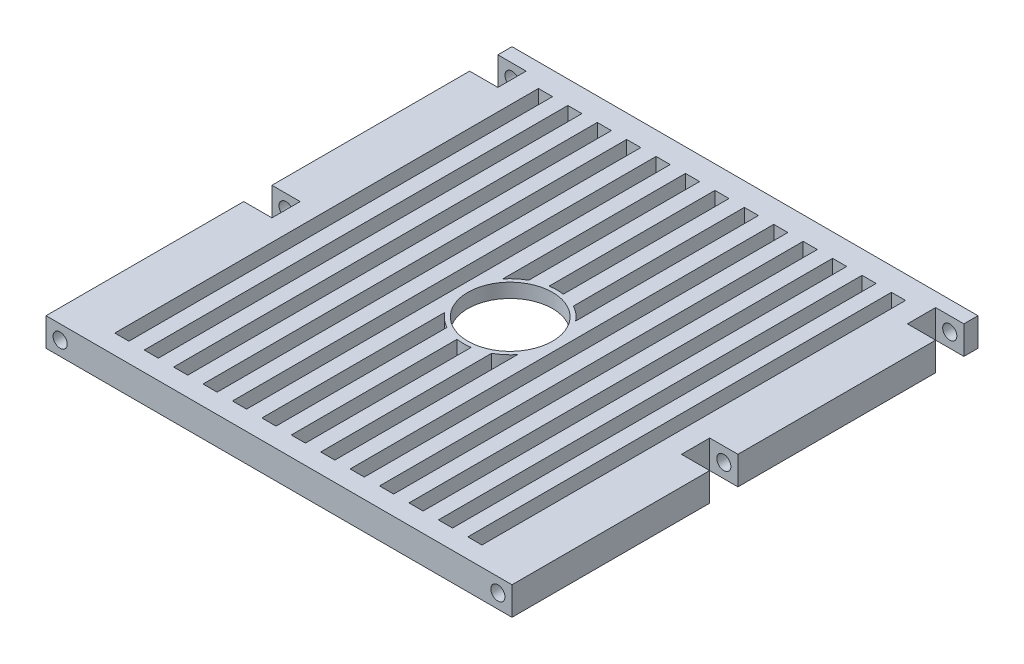
SolidWorks part; units mm, degrees
ref_plane "Plan de face" through (0, 0, 0) normal (0, 0, 1) x (1, 0, 0)
ref_plane "Plan de dessus" through (0, 0, 0) normal (0, 1, 0) x (1, 0, 0)
ref_plane "Plan de droite" through (0, 0, 0) normal (1, 0, 0) x (0, 0, -1)
sketch "Esquisse1" plane through (0, 0, 0) normal (0, 1, 0) x (1, 0, 0)
  line L0 (-82.5, 77.5) -> (-72.5, 77.5)
  line L1 (82.5, 82.5) -> (-82.5, 82.5)
  line L2 (82.5, 82.5) -> (82.5, 77.5)
  line L3 (82.5, -82.5) -> (-82.5, -82.5)
  line L4 (-82.5, 82.5) -> (-82.5, 77.5)
  line L5 (82.5, 82.5) -> (-82.5, -82.5) construction
  line L6 (82.5, -82.5) -> (-82.5, 82.5) construction
  line L7 (-72.5, 77.5) -> (-72.5, 67.5)
  line L8 (-72.5, 67.5) -> (-82.5, 67.5)
  line L9 (-82.5, -2.5) -> (-72.5, -2.5)
  line L10 (-72.5, -2.5) -> (-72.5, -12.5)
  line L11 (-72.5, -12.5) -> (-82.5, -12.5)
  line L12 (-82.5, -2.5) -> (-72.5, -12.5) construction
  line L13 (-72.5, -12.5) -> (-72.5448, -12.5817) construction
  line L14 (-82.5, 67.5) -> (-82.5, -2.5)
  line L15 (-82.5, -12.5) -> (-82.5, -82.5)
  line L16 (0, 16.0212) -> (0, -17.3175) construction
  line L17 (72.5, -12.5) -> (82.5, -12.5)
  line L18 (72.5, -2.5) -> (72.5, -12.5)
  line L19 (82.5, -2.5) -> (72.5, -2.5)
  line L20 (72.5, 77.5) -> (72.5, 67.5)
  line L21 (82.5, 77.5) -> (72.5, 77.5)
  line L22 (72.5, 67.5) -> (82.5, 67.5)
  line L23 (82.5, 67.5) -> (82.5, -2.5)
  line L24 (82.5, -12.5) -> (82.5, -82.5)
  line L25 (60, 74.3519) -> (60, -75.6481)
  line L26 (60, -75.6481) -> (65, -75.6481)
  line L27 (65, 74.3519) -> (65, -75.6481)
  line L28 (65, 74.3519) -> (60, 74.3519)
  line L29 (0, -0.6481) -> (73.9964, -0.6481) construction
  line L30 (49.5833, 74.3519) -> (49.5833, -75.6481)
  line L31 (54.5833, -75.6481) -> (54.5833, 74.3519)
  line L32 (54.5833, 74.3519) -> (49.5833, 74.3519)
  line L33 (49.5833, -75.6481) -> (54.5833, -75.6481)
  line L34 (39.1667, 74.3519) -> (39.1667, -75.6481)
  line L35 (44.1667, -75.6481) -> (44.1667, 74.3519)
  line L36 (44.1667, 74.3519) -> (39.1667, 74.3519)
  line L37 (39.1667, -75.6481) -> (44.1667, -75.6481)
  line L38 (28.75, 74.3519) -> (28.75, -75.6481)
  line L39 (33.75, -75.6481) -> (33.75, 74.3519)
  line L40 (33.75, 74.3519) -> (28.75, 74.3519)
  line L41 (28.75, -75.6481) -> (33.75, -75.6481)
  line L42 (18.3333, 74.3519) -> (18.3333, -75.6481)
  line L43 (23.3333, -75.6481) -> (23.3333, 74.3519)
  line L44 (23.3333, 74.3519) -> (18.3333, 74.3519)
  line L45 (18.3333, -75.6481) -> (23.3333, -75.6481)
  line L46 (7.9167, 74.3519) -> (7.9167, 12.0926)
  line L47 (12.9167, -75.6481) -> (12.9167, -8.2744)
  line L48 (12.9167, 74.3519) -> (7.9167, 74.3519)
  line L49 (7.9167, -75.6481) -> (12.9167, -75.6481)
  line L50 (-2.5, 74.3519) -> (-2.5, 14.1421)
  line L51 (2.5, -75.6481) -> (2.5, -15.4383)
  line L52 (2.5, 74.3519) -> (-2.5, 74.3519)
  line L53 (-2.5, -75.6481) -> (2.5, -75.6481)
  line L54 (-12.9167, 74.3519) -> (-12.9167, 6.9781)
  line L55 (-7.9167, -75.6481) -> (-7.9167, -13.3888)
  line L56 (-7.9167, 74.3519) -> (-12.9167, 74.3519)
  line L57 (-12.9167, -75.6481) -> (-7.9167, -75.6481)
  line L58 (-23.3333, 74.3519) -> (-23.3333, -75.6481)
  line L59 (-18.3333, -75.6481) -> (-18.3333, 74.3519)
  line L60 (-18.3333, 74.3519) -> (-23.3333, 74.3519)
  line L61 (-23.3333, -75.6481) -> (-18.3333, -75.6481)
  line L62 (-33.75, 74.3519) -> (-33.75, -75.6481)
  line L63 (-28.75, -75.6481) -> (-28.75, 74.3519)
  line L64 (-28.75, 74.3519) -> (-33.75, 74.3519)
  line L65 (-33.75, -75.6481) -> (-28.75, -75.6481)
  line L66 (-44.1667, 74.3519) -> (-44.1667, -75.6481)
  line L67 (-39.1667, -75.6481) -> (-39.1667, 74.3519)
  line L68 (-39.1667, 74.3519) -> (-44.1667, 74.3519)
  line L69 (-44.1667, -75.6481) -> (-39.1667, -75.6481)
  line L70 (-54.5833, 74.3519) -> (-54.5833, -75.6481)
  line L71 (-49.5833, -75.6481) -> (-49.5833, 74.3519)
  line L72 (-49.5833, 74.3519) -> (-54.5833, 74.3519)
  line L73 (-54.5833, -75.6481) -> (-49.5833, -75.6481)
  line L74 (-65, 74.3519) -> (-65, -75.6481)
  line L75 (-60, -75.6481) -> (-60, 74.3519)
  line L76 (-60, 74.3519) -> (-65, 74.3519)
  line L77 (-65, -75.6481) -> (-60, -75.6481)
  line L78 (12.9167, 6.9781) -> (12.9167, 74.3519)
  line L79 (7.9167, -13.3888) -> (7.9167, -75.6481)
  line L80 (2.5, 14.1421) -> (2.5, 74.3519)
  line L81 (-12.9167, -8.2744) -> (-12.9167, -75.6481)
  line L82 (-7.9167, 12.0926) -> (-7.9167, 74.3519)
  line L83 (-2.5, -15.4383) -> (-2.5, -75.6481)
  circle A0 centre (0, -0.6481) radius 15
  circle A1 centre (0, -0.6481) radius 16.5
  point P0 (0, 0)
  point P12 (-77.5, -7.5)
  point P32 (60, -0.6481)
  dimension "D9" = 30
  dimension "D15" = 1.5
  dimension "D1" = 165
  dimension "D2" = 165
  dimension "D3" = 5
  dimension "D4" = 10
  dimension "D5" = 10
  dimension "D6" = 10
  dimension "D7" = 10
  dimension "D8" = 90
  dimension "D10" = 5
  dimension "D11" = 150
  dimension "D12" = 60
  dimension "D14" = 65
  dimension "D13" = 13
extrude "BASE" add sketch "Esquisse1" along normal blind 10 contours L24 L17 L18 L19 L23 L22 L20 L21 L2 L1 L4 L0 L7 L8 L14 L9 L10 L11 L15 L3 A0 L51 L53 L83 L55 L57 L81 L54 L56 L82 L50 L52 L80 L46 L48 L78 L47 L49 L79 L77 L74 L76 L75 | L54 A1 L81 A0
sketch "Esquisse5" plane through (0, 0, 12.5) normal (0, 0, -1) x (-1, 0, 0)
  line L0 (-82.5, 10) -> (-72.5, 0) construction
  line L1 (-82.5, 0) -> (82.5, 0) construction
  line L2 (-72.5, 0) -> (-72.5, 10) construction
  line L3 (-82.5, 10) -> (82.5, 10) construction
  line L4 (-72.5, 10) -> (-82.5, 0) construction
  line L5 (-82.5, 10) -> (-82.5, 0) construction
  line L6 (0, 13.0138) -> (0, -4.3994) construction
  line L7 (72.5, 10) -> (82.5, 0) construction
  line L8 (72.5, 0) -> (72.5, 10) construction
  line L9 (82.5, 10) -> (72.5, 0) construction
  circle A0 centre (-77.5, 5) radius 2.5
  circle A1 centre (77.5, 5) radius 2.5
  dimension "D2" = 5
  dimension "D1" = 10
extrude "VIDE VIS" cut sketch "Esquisse5" against normal through all both and the other way through all
sketch "Esquisse6" plane through (0, 0, 0) normal (0, -1, 0) x (1, 0, 0)
  line L1 (65, -74.3519) -> (-65, -74.3519)
  line L2 (65, -74.3519) -> (65, 75.6481)
  line L3 (65, 75.6481) -> (-65, 75.6481)
  line L4 (-65, -74.3519) -> (-65, 75.6481)
  line L5 (65, -74.3519) -> (-65, 75.6481) construction
  line L6 (65, 75.6481) -> (-65, -74.3519) construction
  point P0 (0, 0.6481)
extrude "Enlèv. mat.-Extru.6" cut sketch "Esquisse6" against normal blind 5
